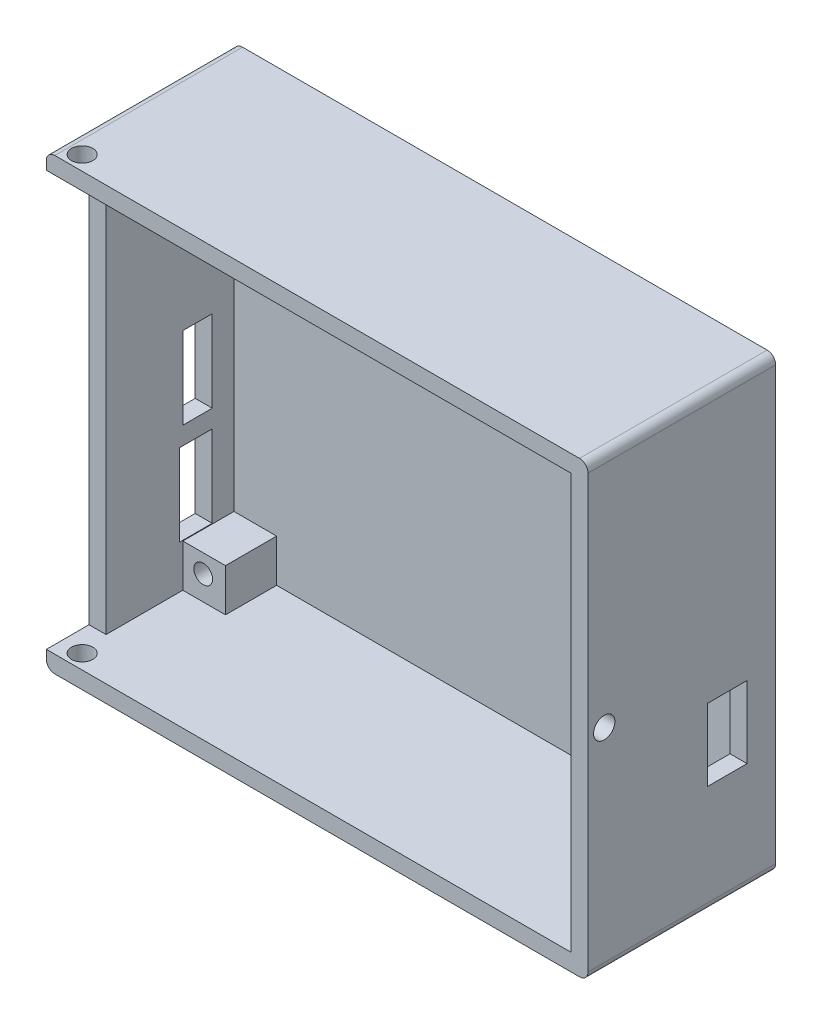
SolidWorks part; units mm, degrees
ref_plane "Front Plane" through (0, 0, 0) normal (0, 0, 1) x (1, 0, 0)
ref_plane "Top Plane" through (0, 0, 0) normal (0, 1, 0) x (1, 0, 0)
ref_plane "Right Plane" through (0, 0, 0) normal (1, 0, 0) x (0, 0, -1)
sketch "Sketch2" plane through (0, 0, 0) normal (0, 0, 1) x (1, 0, 0)
  line L0 (60.065, 78.424) -> (119.572, 78.424)
  line L1 (119.572, 78.424) -> (119.572, 29.78)
  line L2 (119.572, 29.78) -> (60.065, 29.78)
  line L3 (60.065, 29.78) -> (60.065, 78.424)
  line L4 (60.436, 80.424) -> (121.572, 80.424)
  line L5 (121.572, 80.424) -> (121.572, 27.78)
  line L6 (121.572, 27.78) -> (58.065, 27.78)
  line L7 (58.065, 27.78) -> (58.065, 80.424)
  line L8 (58.065, 80.424) -> (60.436, 80.424)
  line L9 (116.332, 77.724) -> (62.865, 77.724) construction
  line L10 (118.872, 33.909) -> (118.872, 75.184) construction
  line L11 (62.738, 30.48) -> (116.713, 30.48) construction
  dimension "D1" = 2
  dimension "D2" = 2
  dimension "D3" = 2
  dimension "D4" = 2
  dimension "D5" = 0.7
  dimension "D6" = 0.7
  dimension "D7" = 0.7
  dimension "D8" = 0.7
extrude "Boss-Extrude1" add sketch "Sketch2" along normal blind 20 from offset 40 offset against normal yes
sketch "Sketch3" plane through (0, 0, -40) normal (0, 0, -1) x (-1, 0, 0)
  line L1 (-121.572, 80.424) -> (-58.065, 80.424)
  line L2 (-121.572, 80.424) -> (-121.572, 27.78)
  line L3 (-121.572, 27.78) -> (-58.065, 27.78)
  line L4 (-58.065, 80.424) -> (-58.065, 27.78)
extrude "Boss-Extrude2" add sketch "Sketch3" along normal blind 2
sketch "Sketch8" plane through (0, 0, 0) normal (0, 0, 1) x (1, 0, 0)
  line L4 (119.572, 29.78) -> (119.572, 78.424)
  line L5 (119.572, 78.424) -> (60.065, 78.424)
  line L6 (60.065, 78.424) -> (60.065, 29.78)
  line L7 (60.065, 29.78) -> (119.572, 29.78)
  line L8 (119.572, 29.78) -> (119.572, 78.424)
  line L9 (119.572, 78.424) -> (60.065, 78.424)
  line L10 (60.065, 78.424) -> (60.065, 29.78)
  line L11 (60.065, 29.78) -> (119.572, 29.78)
  dimension "D1" = 0
sketch "Sketch12" plane through (0, 0, -40) normal (0, 0, 1) x (1, 0, 0)
  line L1 (60.065, 78.424) -> (65.065, 78.424)
  line L2 (60.065, 78.424) -> (60.065, 73.424)
  line L3 (60.065, 73.424) -> (65.065, 73.424)
  line L4 (119.572, 29.78) -> (119.572, 78.424)
  line L5 (119.572, 78.424) -> (60.065, 78.424)
  line L6 (60.065, 78.424) -> (60.065, 29.78)
  line L7 (60.065, 29.78) -> (119.572, 29.78)
  line L8 (119.572, 29.78) -> (119.572, 78.424)
  line L9 (119.572, 78.424) -> (60.065, 78.424)
  line L10 (60.065, 78.424) -> (60.065, 29.78)
  line L11 (60.065, 29.78) -> (119.572, 29.78)
  line L12 (65.065, 78.424) -> (65.065, 73.424)
  line L13 (119.572, 78.424) -> (113.572, 78.424)
  line L14 (119.572, 78.424) -> (119.572, 73.424)
  line L15 (119.572, 73.424) -> (113.572, 73.424)
  line L16 (113.572, 78.424) -> (113.572, 73.424)
  line L17 (119.572, 29.78) -> (114.572, 29.78)
  line L18 (119.572, 29.78) -> (119.572, 35.28)
  line L19 (119.572, 35.28) -> (114.572, 35.28)
  line L20 (114.572, 29.78) -> (114.572, 35.28)
  line L21 (60.065, 29.78) -> (65.065, 29.78)
  line L22 (60.065, 29.78) -> (60.065, 34.78)
  line L23 (60.065, 34.78) -> (65.065, 34.78)
  line L24 (65.065, 29.78) -> (65.065, 34.78)
  circle A0 centre (117.094, 33.147) radius 1 construction
  circle A1 centre (115.905, 75.538) radius 1 construction
  circle A2 centre (62.455, 32.641) radius 1 construction
  circle A3 centre (62.836, 75.44) radius 1 construction
  circle A4 centre (117.094, 33.147) radius 1
  circle A5 centre (115.905, 75.538) radius 1
  circle A6 centre (62.455, 32.641) radius 1
  circle A7 centre (62.836, 75.44) radius 1
  dimension "D2" = 5
  dimension "D3" = 5
  dimension "D4" = 5
  dimension "D5" = 6
  dimension "D6" = 5
  dimension "D7" = 5.5
  dimension "D8" = 5
  dimension "D9" = 5
  dimension "D1" = 0
extrude "Boss-Extrude4" add sketch "Sketch12" along normal blind 6 contours L1 L12 L3 L2 | L21 L24 L23 L22 | L18 L19 L20 L17 | L14 L15 L16 L13
sketch "Sketch20" plane through (0, 0, -34) normal (0, 0, 1) x (1, 0, 0)
  circle A0 centre (115.905, 75.538) radius 1 construction
  circle A1 centre (117.094, 33.147) radius 1 construction
  circle A2 centre (62.455, 32.641) radius 1 construction
  circle A3 centre (62.836, 75.44) radius 1 construction
  circle A4 centre (115.905, 75.538) radius 1 construction
  circle A5 centre (117.094, 33.147) radius 1 construction
  circle A6 centre (62.455, 32.641) radius 1 construction
  circle A7 centre (62.836, 75.44) radius 1 construction
  circle A8 centre (62.836, 75.44) radius 1.1
  circle A9 centre (115.905, 75.538) radius 1.1
  circle A10 centre (117.094, 33.147) radius 1.1
  circle A11 centre (62.455, 32.641) radius 1.1
extrude "Cut-Extrude12" cut sketch "Sketch20" against normal blind 10
sketch "Sketch23" plane through (60.065, 0, 0) normal (1, 0, 0) x (0, 0, -1)
  line L1 (20, 78.424) -> (25, 78.424)
  line L2 (20, 78.424) -> (20, 29.78)
  line L3 (20, 29.78) -> (25, 29.78)
  line L4 (25, 78.424) -> (25, 29.78)
  line L8 (34, 34.78) -> (40, 34.78)
  line L9 (40, 34.78) -> (40, 73.424)
  line L10 (40, 73.424) -> (34, 73.424)
  line L11 (34, 73.424) -> (34, 78.424)
  line L12 (34, 78.424) -> (20, 78.424)
  line L13 (20, 78.424) -> (20, 29.78)
  line L14 (20, 29.78) -> (34, 29.78)
  line L15 (34, 29.78) -> (34, 34.78)
  line L16 (34, 34.78) -> (40, 34.78)
  line L17 (40, 34.78) -> (40, 73.424)
  line L18 (40, 73.424) -> (34, 73.424)
  line L19 (34, 73.424) -> (34, 78.424)
  line L20 (34, 78.424) -> (20, 78.424)
  line L21 (20, 78.424) -> (20, 29.78)
  line L22 (20, 29.78) -> (34, 29.78)
  line L23 (34, 29.78) -> (34, 34.78)
  line M14 (34, 78.424) -> (20, 78.424)
  line M15 (20, 78.424) -> (20, 29.78)
  line M16 (20, 29.78) -> (34, 29.78)
  dimension "D2" = 5
  dimension "D1" = 0
extrude "Cut-Extrude13" cut sketch "Sketch23" against normal blind 5 contours L4 M14 M15 M16
sketch "Sketch25" plane through (0, 80.424, 0) normal (0, 1, 0) x (1, 0, 0)
  line L0 (58.065, 20) -> (58.065, 42) construction
  line L1 (121.572, 20) -> (58.065, 20) construction
  circle A0 centre (60.565, 21.7) radius 1.25
  dimension "D1" = 2.5
  dimension "D2" = 2.5
  dimension "D3" = 1.7
extrude "Cut-Extrude14" cut sketch "Sketch25" against normal blind 73
sketch "Sketch27" plane through (121.572, 0, 0) normal (1, 0, 0) x (0, 0, -1)
  line L1 (34, 49.0456) -> (38.65, 49.0456)
  line L2 (34, 49.0456) -> (34, 40.6021)
  line L3 (34, 40.6021) -> (38.65, 40.6021)
  line L4 (38.65, 49.0456) -> (38.65, 40.6021)
extrude "Cut-Extrude15" cut sketch "Sketch27" against normal blind 3
sketch "Sketch28" plane through (58.065, 0, 0) normal (-1, 0, 0) x (0, 0, 1)
  line L0 (-33.5885, 33.3699) -> (-33.5885, 74.6379) construction
  line L1 (-37.45, 56.139) -> (-34, 56.139)
  line L2 (-37.45, 56.139) -> (-37.45, 46.539)
  line L3 (-37.45, 46.539) -> (-34, 46.539)
  line L4 (-34, 56.139) -> (-34, 46.539)
  line L5 (-37.45, 44.4434) -> (-33.5885, 44.4434)
  line L6 (-37.45, 44.4434) -> (-37.45, 34.8541)
  line L7 (-37.45, 34.8541) -> (-33.5885, 34.8541)
  line L8 (-33.5885, 44.4434) -> (-33.5885, 34.8541)
extrude "Cut-Extrude16" cut sketch "Sketch28" against normal blind 3
sketch "Sketch30" plane through (119.572, 0, 0) normal (1, 0, 0) x (0, 0, -1)
  circle A0 centre (21.9008, 52.6382) radius 1.25
  dimension "D1" = 2.5
extrude "Cut-Extrude24" cut sketch "Sketch30" along normal blind 3
fillet "Fillet1" radius 1 1 edges at (58.065, 80.424, -31)
fillet "Fillet2" radius 1 1 edges at (121.572, 80.424, -31)
fillet "Fillet3" radius 1 1 edges at (121.572, 27.78, -31)
fillet "Fillet4" radius 1 1 edges at (58.065, 27.78, -31)
